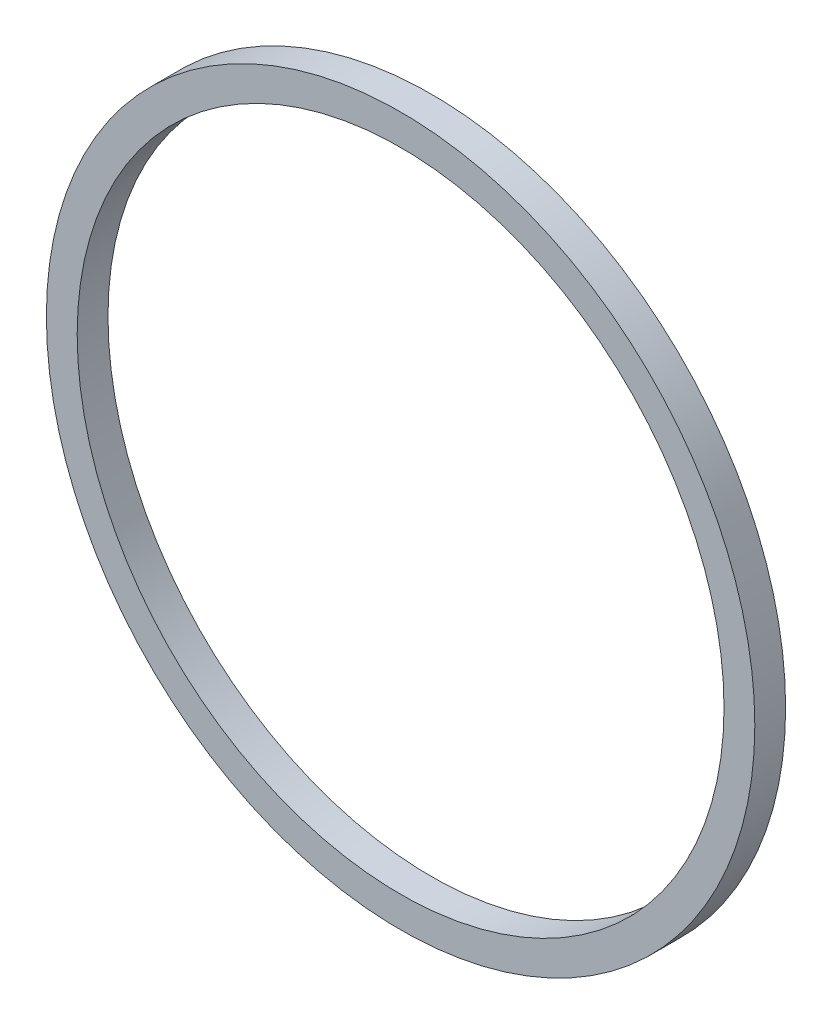
SolidWorks part; units mm, degrees
ref_plane "Ebene vorne" through (0, 0, 0) normal (0, 0, 1) x (1, 0, 0)
ref_plane "Ebene oben" through (0, 0, 0) normal (0, 1, 0) x (1, 0, 0)
ref_plane "Ebene rechts" through (0, 0, 0) normal (1, 0, 0) x (0, 0, -1)
sketch "Skizze1" plane through (0, 0, 0) normal (0, 0, 1) x (1, 0, 0)
  circle A0 centre (0, 0) radius 23
  circle A1 centre (0, 0) radius 21
  dimension "D1" = 46
  dimension "D2" = 42
extrude "Aufsatz-Linear austragen1" add sketch "Skizze1" along normal blind 2
